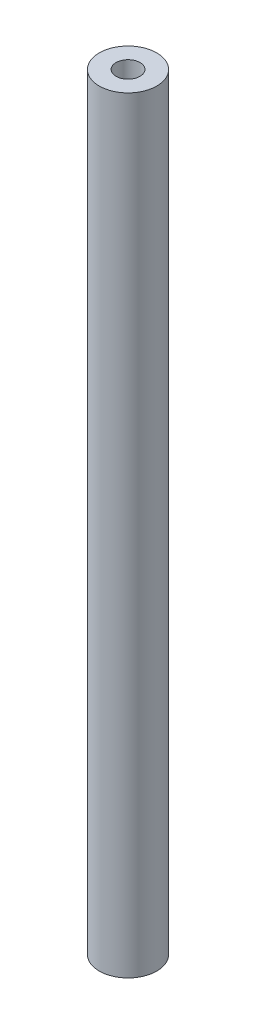
SolidWorks part; units mm, degrees
material "APCP"
ref_plane "Front Plane" through (0, 0, 0) normal (0, 0, 1) x (1, 0, 0)
ref_plane "Top Plane" through (0, 0, 0) normal (0, 1, 0) x (1, 0, 0)
ref_plane "Right Plane" through (0, 0, 0) normal (1, 0, 0) x (0, 0, -1)
sketch "Sketch1" plane through (0, 0, 0) normal (0, 1, 0) x (1, 0, 0)
  circle A0 centre (0, 0) radius 45.72
  dimension "D1" = 91.44
extrude "Boss-Extrude1" add sketch "Sketch1" along normal blind 1219.2
sketch "Sketch2" plane through (0, 1219.2, 0) normal (0, 1, 0) x (1, 0, 0)
  circle A0 centre (0, 0) radius 19.05
  dimension "D1" = 38.1
extrude "Cut-Extrude1" cut sketch "Sketch2" against normal through all
